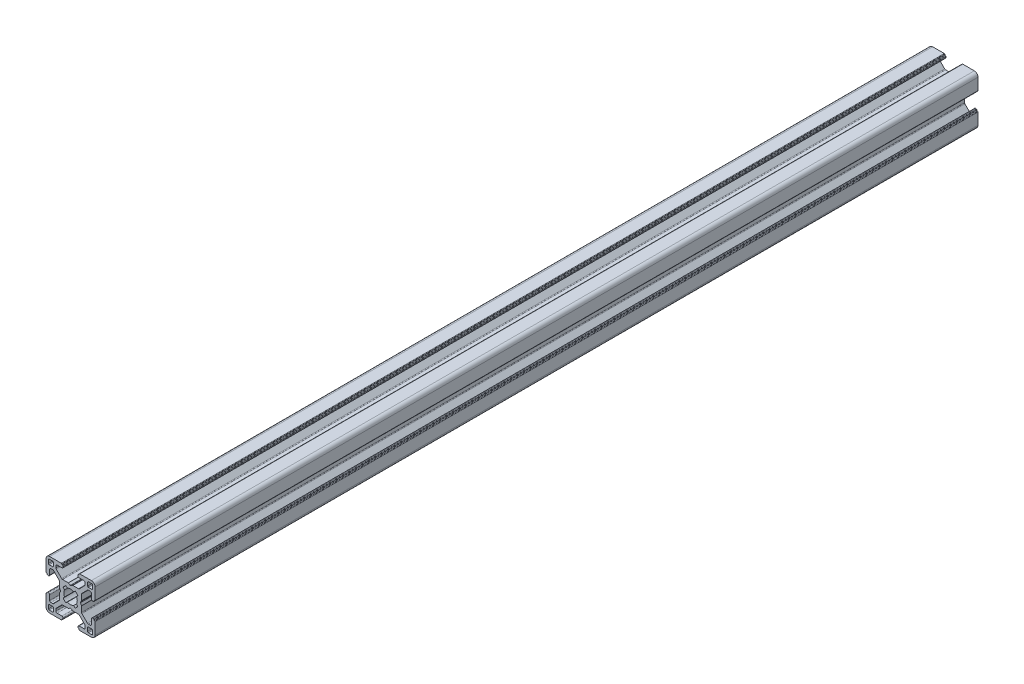
SolidWorks part; units mm, degrees
material "6063-O, Barra estrusa (SS)"
ref_plane "Piano frontale" through (0, 0, 0) normal (0, 0, 1) x (1, 0, 0)
ref_plane "Piano superiore" through (0, 0, 0) normal (0, 1, 0) x (1, 0, 0)
ref_plane "Piano destro" through (0, 0, 0) normal (1, 0, 0) x (0, 0, -1)
ref_plane "Piano1" through (0, 0, 100) normal (0, 0, 1) x (1, 0, 0)
sketch "Schizzo1" plane through (0, 0, 100) normal (0, 0, 1) x (1, 0, 0)
  line L0 (-1.9139, 2.9896) -> (-1.2582, 2.4453)
  line L1 (1.2582, 2.4453) -> (1.9139, 2.9896)
  line L2 (2.9922, 1.9099) -> (2.4453, 1.2582)
  line L3 (2.4453, -1.2582) -> (2.9922, -1.9099)
  line L4 (1.9139, -2.9896) -> (1.2582, -2.4453)
  line L5 (-1.2582, -2.4453) -> (-1.9139, -2.9896)
  line L6 (-2.9922, -1.9099) -> (-2.4453, -1.2582)
  line L7 (-2.4453, 1.2582) -> (-2.9922, 1.9099)
  line L8 (-9.3, 3) -> (-9, 3)
  line L9 (-8.5, 3.5) -> (-8.5, 5.5)
  line L10 (-8, 6) -> (-7.2678, 6)
  line L11 (-6.9142, 5.8536) -> (-4.6464, 3.5858)
  line L12 (-4.5, 3.2322) -> (-4.5, 0.9536)
  line L13 (-4.4732, 0.8536) -> (-4.0381, 0.1)
  line L14 (-4.0381, -0.1) -> (-4.4732, -0.8536)
  line L15 (-4.5, -0.9536) -> (-4.5, -3.2322)
  line L16 (-4.6464, -3.5858) -> (-6.9142, -5.8536)
  line L17 (-7.2678, -6) -> (-8, -6)
  line L18 (-8.5, -5.5) -> (-8.5, -3.5)
  line L19 (-9, -3) -> (-9.3, -3)
  line L20 (-9.5, -3.2) -> (-9.5, -3.35)
  line L21 (-9.7, -3.55) -> (-9.8, -3.55)
  line L22 (-10, -3.75) -> (-10, -8.5)
  line L23 (-8.5, -10) -> (-3.75, -10)
  line L24 (-3.55, -9.8) -> (-3.55, -9.7)
  line L25 (-3.35, -9.5) -> (-3.2, -9.5)
  line L26 (-3, -9.3) -> (-3, -9)
  line L27 (-3.5, -8.5) -> (-5.5, -8.5)
  line L28 (-6, -8) -> (-6, -7.2678)
  line L29 (-5.8536, -6.9142) -> (-3.5858, -4.6464)
  line L30 (-3.2322, -4.5) -> (-0.9536, -4.5)
  line L31 (-0.8536, -4.4732) -> (-0.1, -4.0381)
  line L32 (0.1, -4.0381) -> (0.8536, -4.4732)
  line L33 (0.9536, -4.5) -> (3.2322, -4.5)
  line L34 (3.5858, -4.6464) -> (5.8536, -6.9142)
  line L35 (6, -7.2678) -> (6, -8)
  line L36 (5.5, -8.5) -> (3.5, -8.5)
  line L37 (3, -9) -> (3, -9.3)
  line L38 (3.2, -9.5) -> (3.35, -9.5)
  line L39 (3.55, -9.7) -> (3.55, -9.8)
  line L40 (3.75, -10) -> (8.5, -10)
  line L41 (10, -8.5) -> (10, -3.75)
  line L42 (9.8, -3.55) -> (9.7, -3.55)
  line L43 (9.5, -3.35) -> (9.5, -3.2)
  line L44 (9.3, -3) -> (9, -3)
  line L45 (8.5, -3.5) -> (8.5, -5.5)
  line L46 (8, -6) -> (7.2678, -6)
  line L47 (6.9142, -5.8536) -> (4.6464, -3.5858)
  line L48 (4.5, -3.2322) -> (4.5, -0.9536)
  line L49 (4.4732, -0.8536) -> (4.0381, -0.1)
  line L50 (4.0381, 0.1) -> (4.4732, 0.8536)
  line L51 (4.5, 0.9536) -> (4.5, 3.2322)
  line L52 (4.6464, 3.5858) -> (6.9142, 5.8536)
  line L53 (7.2678, 6) -> (8, 6)
  line L54 (8.5, 5.5) -> (8.5, 3.5)
  line L55 (9, 3) -> (9.3, 3)
  line L56 (9.5, 3.2) -> (9.5, 3.35)
  line L57 (9.7, 3.55) -> (9.8, 3.55)
  line L58 (10, 3.75) -> (10, 8.5)
  line L59 (8.5, 10) -> (3.75, 10)
  line L60 (3.55, 9.8) -> (3.55, 9.7)
  line L61 (3.35, 9.5) -> (3.2, 9.5)
  line L62 (3, 9.3) -> (3, 9)
  line L63 (3.5, 8.5) -> (5.5, 8.5)
  line L64 (6, 8) -> (6, 7.2678)
  line L65 (5.8536, 6.9142) -> (3.5858, 4.6464)
  line L66 (3.2322, 4.5) -> (0.9536, 4.5)
  line L67 (0.8536, 4.4732) -> (0.1, 4.0381)
  line L68 (-0.1, 4.0381) -> (-0.8536, 4.4732)
  line L69 (-0.9536, 4.5) -> (-3.2322, 4.5)
  line L70 (-3.5858, 4.6464) -> (-5.8536, 6.9142)
  line L71 (-6, 7.2678) -> (-6, 8)
  line L72 (-5.5, 8.5) -> (-3.5, 8.5)
  line L73 (-3, 9) -> (-3, 9.3)
  line L74 (-3.2, 9.5) -> (-3.35, 9.5)
  line L75 (-3.55, 9.7) -> (-3.55, 9.8)
  line L76 (-3.75, 10) -> (-8.5, 10)
  line L77 (-10, 8.5) -> (-10, 3.75)
  line L78 (-9.8, 3.55) -> (-9.7, 3.55)
  line L79 (-9.5, 3.35) -> (-9.5, 3.2)
  line L80 (8.7, 7) -> (7.3, 7)
  line L81 (-7.3, 7) -> (-8.7, 7)
  line L82 (-7, 7.3) -> (-7, 8.7)
  line L83 (-7.3, 9) -> (-8.7, 9)
  line L84 (-9, 7.3) -> (-9, 8.7)
  line L85 (9, 7.3) -> (9, 8.7)
  line L86 (8.7, 9) -> (7.3, 9)
  line L87 (7, 7.3) -> (7, 8.7)
  line L88 (8.7, -9) -> (7.3, -9)
  line L89 (9, -8.7) -> (9, -7.3)
  line L90 (8.7, -7) -> (7.3, -7)
  line L91 (7, -8.7) -> (7, -7.3)
  line L92 (-7.3, -9) -> (-8.7, -9)
  line L93 (-7, -8.7) -> (-7, -7.3)
  line L94 (-7.3, -7) -> (-8.7, -7)
  line L95 (-9, -8.7) -> (-9, -7.3)
  arc A0 (-1.2582, 2.4453) -> (1.2582, 2.4453) centre (0, 0) cw
  arc A1 (1.9139, 2.9896) -> (2.9922, 1.9099) centre (0, 0) cw
  arc A2 (2.4453, 1.2582) -> (2.4453, -1.2582) centre (0, 0) cw
  arc A3 (2.9922, -1.9099) -> (1.9139, -2.9896) centre (0, 0) cw
  arc A4 (1.2582, -2.4453) -> (-1.2582, -2.4453) centre (0, 0) cw
  arc A5 (-1.9139, -2.9896) -> (-2.9922, -1.9099) centre (0, 0) cw
  arc A6 (-2.4453, -1.2582) -> (-2.4453, 1.2582) centre (0, 0) cw
  arc A7 (-2.9922, 1.9099) -> (-1.9139, 2.9896) centre (0, 0) cw
  arc A8 (-9.5, 3.2) -> (-9.3, 3) centre (-9.3, 3.2) ccw
  arc A9 (-9, 3) -> (-8.5, 3.5) centre (-9, 3.5) ccw
  arc A10 (-8.5, 5.5) -> (-8, 6) centre (-8, 5.5) cw
  arc A11 (-7.2678, 6) -> (-6.9142, 5.8536) centre (-7.2678, 5.5) cw
  arc A12 (-4.6464, 3.5858) -> (-4.5, 3.2322) centre (-5, 3.2322) cw
  arc A13 (-4.5, 0.9536) -> (-4.4732, 0.8536) centre (-4.3, 0.9536) ccw
  arc A14 (-4.0381, 0.1) -> (-4.0381, -0.1) centre (-4.2113, 0) cw
  arc A15 (-4.4732, -0.8536) -> (-4.5, -0.9536) centre (-4.3, -0.9536) ccw
  arc A16 (-4.5, -3.2322) -> (-4.6464, -3.5858) centre (-5, -3.2322) cw
  arc A17 (-6.9142, -5.8536) -> (-7.2678, -6) centre (-7.2678, -5.5) cw
  arc A18 (-8, -6) -> (-8.5, -5.5) centre (-8, -5.5) cw
  arc A19 (-8.5, -3.5) -> (-9, -3) centre (-9, -3.5) ccw
  arc A20 (-9.3, -3) -> (-9.5, -3.2) centre (-9.3, -3.2) ccw
  arc A21 (-9.5, -3.35) -> (-9.7, -3.55) centre (-9.7, -3.35) cw
  arc A22 (-9.8, -3.55) -> (-10, -3.75) centre (-9.8, -3.75) ccw
  arc A23 (-10, -8.5) -> (-8.5, -10) centre (-8.5, -8.5) ccw
  arc A24 (-3.75, -10) -> (-3.55, -9.8) centre (-3.75, -9.8) ccw
  arc A25 (-3.55, -9.7) -> (-3.35, -9.5) centre (-3.35, -9.7) cw
  arc A26 (-3.2, -9.5) -> (-3, -9.3) centre (-3.2, -9.3) ccw
  arc A27 (-3, -9) -> (-3.5, -8.5) centre (-3.5, -9) ccw
  arc A28 (-5.5, -8.5) -> (-6, -8) centre (-5.5, -8) cw
  arc A29 (-6, -7.2678) -> (-5.8536, -6.9142) centre (-5.5, -7.2678) cw
  arc A30 (-3.5858, -4.6464) -> (-3.2322, -4.5) centre (-3.2322, -5) cw
  arc A31 (-0.9536, -4.5) -> (-0.8536, -4.4732) centre (-0.9536, -4.3) ccw
  arc A32 (-0.1, -4.0381) -> (0.1, -4.0381) centre (0, -4.2113) cw
  arc A33 (0.8536, -4.4732) -> (0.9536, -4.5) centre (0.9536, -4.3) ccw
  arc A34 (3.2322, -4.5) -> (3.5858, -4.6464) centre (3.2322, -5) cw
  arc A35 (5.8536, -6.9142) -> (6, -7.2678) centre (5.5, -7.2678) cw
  arc A36 (6, -8) -> (5.5, -8.5) centre (5.5, -8) cw
  arc A37 (3.5, -8.5) -> (3, -9) centre (3.5, -9) ccw
  arc A38 (3, -9.3) -> (3.2, -9.5) centre (3.2, -9.3) ccw
  arc A39 (3.35, -9.5) -> (3.55, -9.7) centre (3.35, -9.7) cw
  arc A40 (3.55, -9.8) -> (3.75, -10) centre (3.75, -9.8) ccw
  arc A41 (8.5, -10) -> (10, -8.5) centre (8.5, -8.5) ccw
  arc A42 (10, -3.75) -> (9.8, -3.55) centre (9.8, -3.75) ccw
  arc A43 (9.7, -3.55) -> (9.5, -3.35) centre (9.7, -3.35) cw
  arc A44 (9.5, -3.2) -> (9.3, -3) centre (9.3, -3.2) ccw
  arc A45 (9, -3) -> (8.5, -3.5) centre (9, -3.5) ccw
  arc A46 (8.5, -5.5) -> (8, -6) centre (8, -5.5) cw
  arc A47 (7.2678, -6) -> (6.9142, -5.8536) centre (7.2678, -5.5) cw
  arc A48 (4.6464, -3.5858) -> (4.5, -3.2322) centre (5, -3.2322) cw
  arc A49 (4.5, -0.9536) -> (4.4732, -0.8536) centre (4.3, -0.9536) ccw
  arc A50 (4.0381, -0.1) -> (4.0381, 0.1) centre (4.2113, 0) cw
  arc A51 (4.4732, 0.8536) -> (4.5, 0.9536) centre (4.3, 0.9536) ccw
  arc A52 (4.5, 3.2322) -> (4.6464, 3.5858) centre (5, 3.2322) cw
  arc A53 (6.9142, 5.8536) -> (7.2678, 6) centre (7.2678, 5.5) cw
  arc A54 (8, 6) -> (8.5, 5.5) centre (8, 5.5) cw
  arc A55 (8.5, 3.5) -> (9, 3) centre (9, 3.5) ccw
  arc A56 (9.3, 3) -> (9.5, 3.2) centre (9.3, 3.2) ccw
  arc A57 (9.5, 3.35) -> (9.7, 3.55) centre (9.7, 3.35) cw
  arc A58 (9.8, 3.55) -> (10, 3.75) centre (9.8, 3.75) ccw
  arc A59 (10, 8.5) -> (8.5, 10) centre (8.5, 8.5) ccw
  arc A60 (3.75, 10) -> (3.55, 9.8) centre (3.75, 9.8) ccw
  arc A61 (3.55, 9.7) -> (3.35, 9.5) centre (3.35, 9.7) cw
  arc A62 (3.2, 9.5) -> (3, 9.3) centre (3.2, 9.3) ccw
  arc A63 (3, 9) -> (3.5, 8.5) centre (3.5, 9) ccw
  arc A64 (5.5, 8.5) -> (6, 8) centre (5.5, 8) cw
  arc A65 (6, 7.2678) -> (5.8536, 6.9142) centre (5.5, 7.2678) cw
  arc A66 (3.5858, 4.6464) -> (3.2322, 4.5) centre (3.2322, 5) cw
  arc A67 (0.9536, 4.5) -> (0.8536, 4.4732) centre (0.9536, 4.3) ccw
  arc A68 (0.1, 4.0381) -> (-0.1, 4.0381) centre (0, 4.2113) cw
  arc A69 (-0.8536, 4.4732) -> (-0.9536, 4.5) centre (-0.9536, 4.3) ccw
  arc A70 (-3.2322, 4.5) -> (-3.5858, 4.6464) centre (-3.2322, 5) cw
  arc A71 (-5.8536, 6.9142) -> (-6, 7.2678) centre (-5.5, 7.2678) cw
  arc A72 (-6, 8) -> (-5.5, 8.5) centre (-5.5, 8) cw
  arc A73 (-3.5, 8.5) -> (-3, 9) centre (-3.5, 9) ccw
  arc A74 (-3, 9.3) -> (-3.2, 9.5) centre (-3.2, 9.3) ccw
  arc A75 (-3.35, 9.5) -> (-3.55, 9.7) centre (-3.35, 9.7) cw
  arc A76 (-3.55, 9.8) -> (-3.75, 10) centre (-3.75, 9.8) ccw
  arc A77 (-8.5, 10) -> (-10, 8.5) centre (-8.5, 8.5) ccw
  arc A78 (-10, 3.75) -> (-9.8, 3.55) centre (-9.8, 3.75) ccw
  arc A79 (-9.7, 3.55) -> (-9.5, 3.35) centre (-9.7, 3.35) cw
  arc A80 (-8.7, 7) -> (-9, 7.3) centre (-8.7, 7.3) cw
  arc A81 (-7, 8.7) -> (-7.3, 9) centre (-7.3, 8.7) ccw
  arc A82 (-7.3, 7) -> (-7, 7.3) centre (-7.3, 7.3) ccw
  arc A83 (-8.7, 9) -> (-9, 8.7) centre (-8.7, 8.7) ccw
  arc A84 (7.3, 7) -> (7, 7.3) centre (7.3, 7.3) cw
  arc A85 (9, 8.7) -> (8.7, 9) centre (8.7, 8.7) ccw
  arc A86 (8.7, 7) -> (9, 7.3) centre (8.7, 7.3) ccw
  arc A87 (7.3, 9) -> (7, 8.7) centre (7.3, 8.7) ccw
  arc A88 (7.3, -9) -> (7, -8.7) centre (7.3, -8.7) cw
  arc A89 (9, -7.3) -> (8.7, -7) centre (8.7, -7.3) ccw
  arc A90 (8.7, -9) -> (9, -8.7) centre (8.7, -8.7) ccw
  arc A91 (7.3, -7) -> (7, -7.3) centre (7.3, -7.3) ccw
  arc A92 (-8.7, -9) -> (-9, -8.7) centre (-8.7, -8.7) cw
  arc A93 (-7, -7.3) -> (-7.3, -7) centre (-7.3, -7.3) ccw
  arc A94 (-7.3, -9) -> (-7, -8.7) centre (-7.3, -8.7) ccw
  arc A95 (-8.7, -7) -> (-9, -7.3) centre (-8.7, -7.3) ccw
  dimension "D1" = 0.3
  dimension "D2" = 1
  dimension "D3" = 1
  dimension "D4" = 1
  dimension "D7" = 1
  dimension "D8" = 1
  dimension "D9" = 1
  dimension "D10" = 1
  dimension "D5" = 2
  dimension "D6" = 2
extrude "Estrusione-Estrusione1" add sketch "Schizzo1" against normal blind 360
